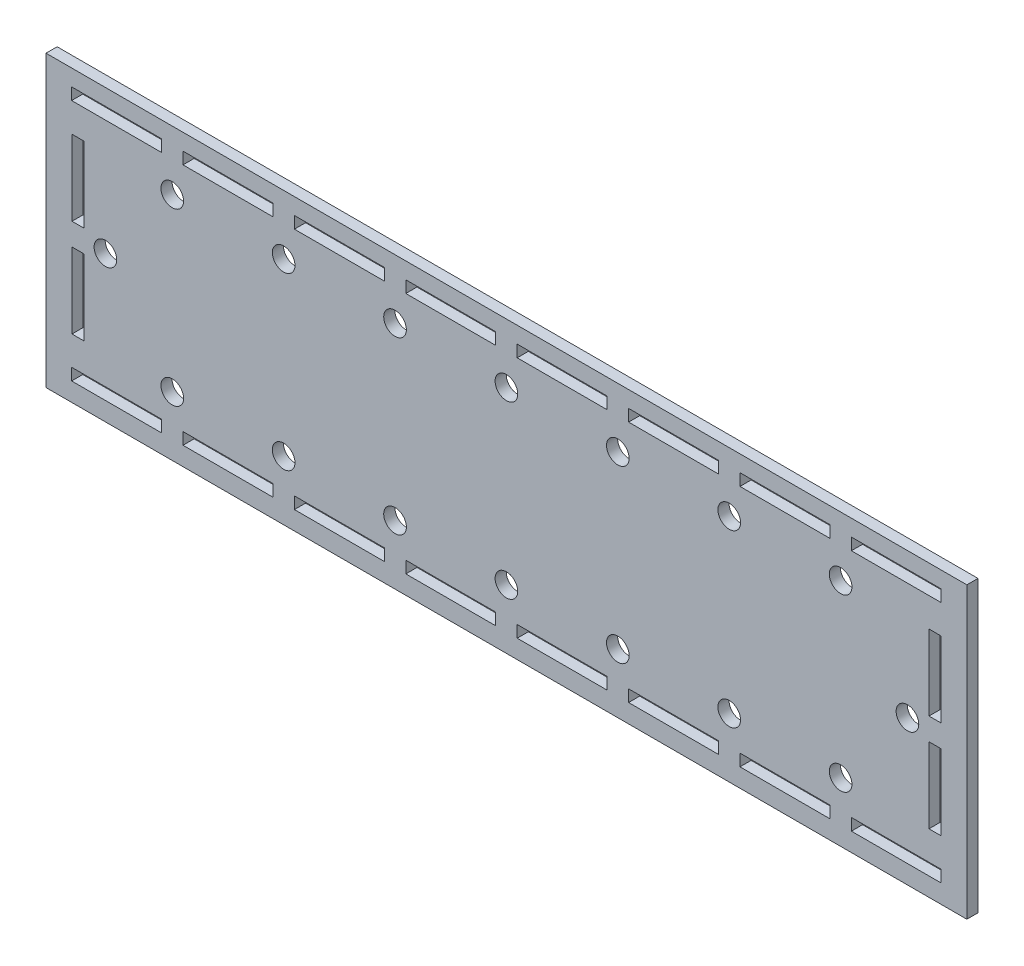
SolidWorks part; units mm, degrees
ref_plane "Front Plane" through (0, 0, 0) normal (0, 0, 1) x (1, 0, 0)
ref_plane "Top Plane" through (0, 0, 0) normal (0, 1, 0) x (1, 0, 0)
ref_plane "Right Plane" through (0, 0, 0) normal (1, 0, 0) x (0, 0, -1)
sketch "Sketch1" plane through (0, 0, 0) normal (0, 0, 1) x (-1, 0, 0)
  line L0 (-395.8872, 493) -> (-395.8872, 489.8)
  line L2 (-395.8872, 493) -> (-371.6872, 493)
  line L3 (-371.6872, 493) -> (-371.6872, 489.8)
  line L4 (-395.8872, 489.8) -> (-371.6872, 489.8)
  line L8 (-425.8872, 493) -> (-425.8872, 489.8)
  line L9 (-552.7872, 498) -> (-304.7872, 498)
  line L10 (-552.7872, 498) -> (-552.7872, 420)
  line L11 (-552.7872, 420) -> (-304.7872, 420)
  line L12 (-304.7872, 498) -> (-304.7872, 420)
  line L13 (-365.8872, 493) -> (-341.6872, 493)
  line L14 (-365.8872, 493) -> (-365.8872, 489.8)
  line L15 (-365.8872, 489.8) -> (-341.6872, 489.8)
  line L16 (-341.6872, 493) -> (-341.6872, 489.8)
  line L17 (-425.8872, 493) -> (-401.6872, 493)
  line L18 (-401.6872, 493) -> (-401.6872, 489.8)
  line L19 (-425.8872, 489.8) -> (-401.6872, 489.8)
  line L20 (-455.8872, 493) -> (-455.8872, 489.8)
  line L21 (-455.8872, 493) -> (-431.6872, 493)
  line L22 (-431.6872, 493) -> (-431.6872, 489.8)
  line L23 (-455.8872, 489.8) -> (-431.6872, 489.8)
  line L24 (-485.8872, 493) -> (-485.8872, 489.8)
  line L25 (-485.8872, 493) -> (-461.6872, 493)
  line L26 (-461.6872, 493) -> (-461.6872, 489.8)
  line L27 (-485.8872, 489.8) -> (-461.6872, 489.8)
  line L28 (-515.8872, 493) -> (-515.8872, 489.8)
  line L29 (-515.8872, 493) -> (-491.6872, 493)
  line L30 (-491.6872, 493) -> (-491.6872, 489.8)
  line L31 (-515.8872, 489.8) -> (-491.6872, 489.8)
  line L32 (-545.8872, 493) -> (-545.8872, 489.8)
  line L33 (-545.8872, 493) -> (-521.6872, 493)
  line L34 (-521.6872, 493) -> (-521.6872, 489.8)
  line L35 (-545.8872, 489.8) -> (-521.6872, 489.8)
  line L36 (-335.8872, 493) -> (-335.8872, 489.8)
  line L37 (-335.8872, 493) -> (-311.6872, 493)
  line L38 (-311.6872, 493) -> (-311.6872, 489.8)
  line L39 (-335.8872, 489.8) -> (-311.6872, 489.8)
  line L40 (-552.7872, 459) -> (-513.2251, 459) construction
  line L73 (-314.9872, 455.7) -> (-311.7872, 455.7)
  line L74 (-314.9872, 482) -> (-311.7872, 482)
  line L75 (-314.9872, 482) -> (-314.9872, 461.7)
  line L76 (-314.9872, 461.7) -> (-311.7872, 461.7)
  line L77 (-311.7872, 482) -> (-311.7872, 461.7)
  line L78 (-311.7872, 435.4) -> (-311.7872, 455.7)
  line L79 (-314.9872, 435.4) -> (-311.7872, 435.4)
  line L80 (-314.9872, 435.4) -> (-314.9872, 455.7)
  line L81 (-428.7872, 510.2561) -> (-428.7872, 380.3241) construction
  line L82 (-542.5872, 435.4) -> (-542.5872, 455.7)
  line L83 (-542.5872, 435.4) -> (-545.7872, 435.4)
  line L84 (-545.7872, 435.4) -> (-545.7872, 455.7)
  line L85 (-542.5872, 455.7) -> (-545.7872, 455.7)
  line L86 (-542.5872, 461.7) -> (-545.7872, 461.7)
  line L87 (-545.7872, 482) -> (-545.7872, 461.7)
  line L88 (-542.5872, 482) -> (-545.7872, 482)
  line L89 (-542.5872, 482) -> (-542.5872, 461.7)
  line L90 (-545.8872, 424.4) -> (-521.6872, 424.4)
  line L91 (-521.6872, 424.4) -> (-521.6872, 427.6)
  line L92 (-545.8872, 427.6) -> (-521.6872, 427.6)
  line L93 (-545.8872, 424.4) -> (-545.8872, 427.6)
  line L94 (-515.8872, 424.4) -> (-491.6872, 424.4)
  line L95 (-491.6872, 424.4) -> (-491.6872, 427.6)
  line L96 (-515.8872, 427.6) -> (-491.6872, 427.6)
  line L97 (-515.8872, 424.4) -> (-515.8872, 427.6)
  line L98 (-485.8872, 424.4) -> (-461.6872, 424.4)
  line L99 (-461.6872, 424.4) -> (-461.6872, 427.6)
  line L100 (-485.8872, 427.6) -> (-461.6872, 427.6)
  line L101 (-485.8872, 424.4) -> (-485.8872, 427.6)
  line L102 (-455.8872, 424.4) -> (-431.6872, 424.4)
  line L103 (-431.6872, 424.4) -> (-431.6872, 427.6)
  line L104 (-455.8872, 427.6) -> (-431.6872, 427.6)
  line L105 (-455.8872, 424.4) -> (-455.8872, 427.6)
  line L106 (-425.8872, 424.4) -> (-401.6872, 424.4)
  line L107 (-401.6872, 424.4) -> (-401.6872, 427.6)
  line L108 (-425.8872, 427.6) -> (-401.6872, 427.6)
  line L109 (-425.8872, 424.4) -> (-425.8872, 427.6)
  line L110 (-395.8872, 424.4) -> (-371.6872, 424.4)
  line L111 (-371.6872, 424.4) -> (-371.6872, 427.6)
  line L112 (-395.8872, 427.6) -> (-371.6872, 427.6)
  line L113 (-395.8872, 424.4) -> (-395.8872, 427.6)
  line L114 (-365.8872, 427.6) -> (-341.6872, 427.6)
  line L115 (-341.6872, 424.4) -> (-341.6872, 427.6)
  line L116 (-365.8872, 424.4) -> (-341.6872, 424.4)
  line L117 (-365.8872, 424.4) -> (-365.8872, 427.6)
  line L118 (-335.8872, 424.4) -> (-311.6872, 424.4)
  line L119 (-311.6872, 424.4) -> (-311.6872, 427.6)
  line L120 (-335.8872, 427.6) -> (-311.6872, 427.6)
  line L121 (-335.8872, 424.4) -> (-335.8872, 427.6)
  circle A16 centre (-338.7872, 436) radius 3.05
  circle A17 centre (-368.7872, 436) radius 3.05
  circle A18 centre (-428.7872, 436) radius 3.05
  circle A19 centre (-398.7872, 436) radius 3.05
  circle A20 centre (-488.7872, 436) radius 3.05
  circle A21 centre (-458.7872, 436) radius 3.05
  circle A22 centre (-458.7872, 482) radius 3.05
  circle A23 centre (-428.7872, 482) radius 3.05
  circle A24 centre (-398.7872, 482) radius 3.05
  circle A25 centre (-368.7872, 482) radius 3.05
  circle A26 centre (-338.7872, 482) radius 3.05
  circle A27 centre (-320.7872, 458.7) radius 3.05
  circle A28 centre (-488.7872, 482) radius 3.05
  circle A29 centre (-518.7872, 436) radius 3.05
  circle A30 centre (-536.7872, 459) radius 3.05
  circle A31 centre (-518.7872, 482) radius 3.05
  point P107 (-313.3872, 482)
  dimension "D4" = 16
  dimension "D11" = 3
  dimension "D1" = 16
  dimension "D2" = 16
  dimension "D3" = 7
  dimension "D5" = 2.9
  dimension "D6" = 2.9
  dimension "D7" = 5
  dimension "D8" = 3.2
  dimension "D14" = 3.2
  dimension "D9" = 7
  dimension "D10" = 2
extrude "Boss-Extrude2" add sketch "Sketch1" along normal blind 3
sketch "Sketch4" plane through (545.7872, 0, 0) normal (-1, 0, 0) x (0, 0, 1)
  line L0 (3, -427.6) -> (10, -427.6)
  line L3 (3, -427.6) -> (3, -435.4)
  line L4 (0, -435.4) -> (0, -455.7)
  line L5 (0, -455.7) -> (3, -455.7)
  line L6 (3, -455.7) -> (3, -435.4)
  line L7 (3, -435.4) -> (0, -435.4)
  line L8 (0, -435.4) -> (0, -455.7)
  line L9 (0, -455.7) -> (3, -455.7)
  line L11 (3, -435.4) -> (0, -435.4)
  line L12 (0, -461.7) -> (0, -482)
  line L13 (0, -482) -> (3, -482)
  line L14 (3, -482) -> (3, -461.7)
  line L15 (3, -461.7) -> (0, -461.7)
  line L17 (0, -482) -> (3, -482)
  line L19 (3, -461.7) -> (0, -461.7)
  line L20 (10, -427.6) -> (10, -489.8)
  line L22 (3, -455.7) -> (3, -461.7)
  line L23 (0, -461.7) -> (0, -482)
  line L24 (3, -482) -> (3, -489.8)
  line L25 (3, -489.8) -> (10, -489.8)
  dimension "D1" = 0
  dimension "D2" = 0
